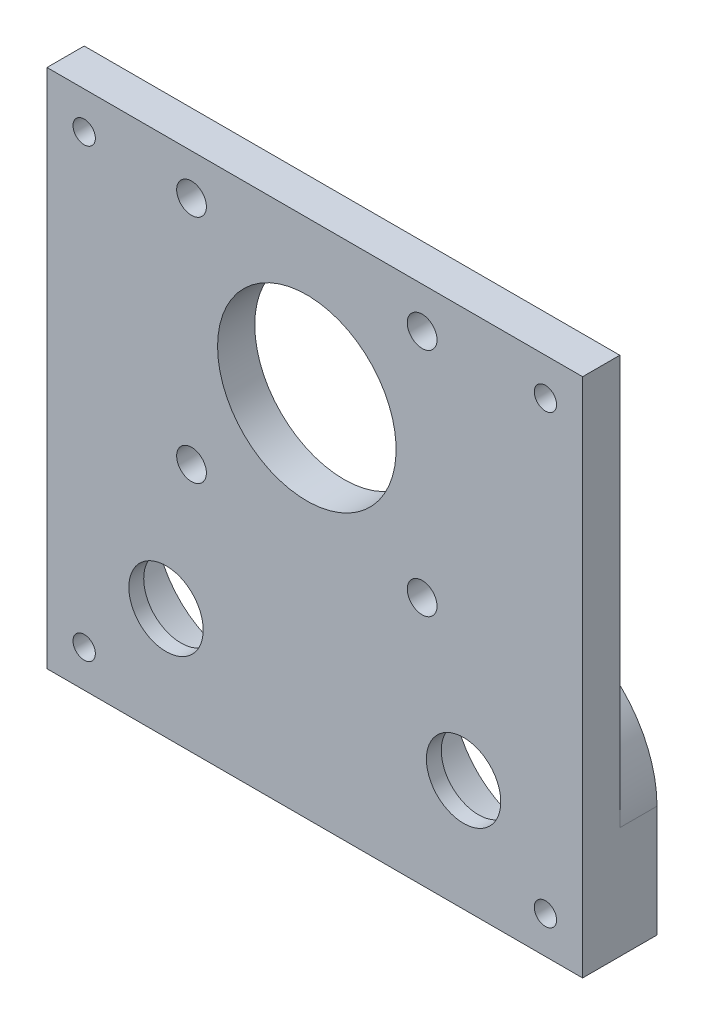
SolidWorks part; units mm, degrees
ref_plane "Front Plane" through (0, 0, 0) normal (0, 0, 1) x (1, 0, 0)
ref_plane "Top Plane" through (0, 0, 0) normal (0, 1, 0) x (1, 0, 0)
ref_plane "Right Plane" through (0, 0, 0) normal (1, 0, 0) x (0, 0, -1)
sketch "Sketch1" plane through (0, 0, 0) normal (0, 0, 1) x (1, 0, 0)
  line L1 (0, 0) -> (70, 0)
  line L2 (0, 0) -> (0, 70)
  line L3 (0, 70) -> (70, 70)
  line L4 (70, 0) -> (70, 70)
  dimension "D1" = 70
  dimension "D2" = 70
extrude "Boss-Extrude1" add sketch "Sketch1" along normal blind 10
sketch "Sketch2" plane through (0, 0, 10) normal (0, 0, 1) x (1, 0, 0)
  line L0 (70, 70) -> (0, 70) construction
  circle A0 centre (35, 49) radius 12
  circle A1 centre (19.5, 65) radius 2
  circle A2 centre (50.5, 65) radius 2
  circle A3 centre (19.5, 34) radius 2
  circle A4 centre (50.5, 34) radius 2
  circle A5 centre (15, 15) radius 11.5
  circle A6 centre (55, 15) radius 11.5
  point P17 (35, 70)
  dimension "D1" = 24
  dimension "D2" = 4
  dimension "D3" = 4
  dimension "D4" = 4
  dimension "D5" = 4
  dimension "D15" = 23
  dimension "D16" = 23
  dimension "D6" = 21
  dimension "D7" = 5
  dimension "D8" = 5
  dimension "D9" = 31
  dimension "D10" = 31
  dimension "D11" = 31
  dimension "D12" = 31
  dimension "D13" = 15.5
  dimension "D14" = 0
  dimension "D17" = 40
  dimension "D18" = 15
  dimension "D19" = 15
  dimension "D20" = 15
extrude "Cut-Extrude1" cut sketch "Sketch2" against normal blind 10
sketch "Sketch3" plane through (0, 0, 0) normal (-1, 0, 0) x (0, 0, 1)
  line L1 (0, 70) -> (10, 70)
  line L2 (0, 70) -> (0, 0)
  line L3 (0, 0) -> (10, 0)
  line L4 (10, 70) -> (10, 0)
extrude "Boss-Extrude2" add sketch "Sketch3" along normal blind 15
sketch "Sketch4" plane through (70, 0, 0) normal (1, 0, 0) x (0, 0, -1)
  line L1 (0, 70) -> (-10, 70)
  line L2 (0, 70) -> (0, 0)
  line L3 (0, 0) -> (-10, 0)
  line L4 (-10, 70) -> (-10, 0)
extrude "Boss-Extrude3" add sketch "Sketch4" along normal blind 15 contours L4 L3 L2 L1
sketch "Sketch5" plane through (0, 0, 10) normal (0, 0, 1) x (1, 0, 0)
  circle A0 centre (15, 15) radius 11.5
  circle A1 centre (55, 15) radius 11.5
  circle A2 centre (15, 15) radius 4
  circle A3 centre (55, 15) radius 4
  dimension "D1" = 8
  dimension "D2" = 8
extrude "Boss-Extrude4" add sketch "Sketch5" against normal blind 2
sketch "Sketch6" plane through (0, 0, 0) normal (0, 0, -1) x (-1, 0, 0)
  line L0 (-85, 70) -> (-85, 0) construction
  line L1 (-85, 70) -> (15, 70) construction
  circle A0 centre (-80, 65) radius 1.5
  circle A1 centre (-80, 5) radius 1.5
  circle A2 centre (10, 65) radius 1.6487
  circle A3 centre (10, 5) radius 1.5
  dimension "D4" = 3
  dimension "D5" = 3
  dimension "D8" = 3
  dimension "D1" = 5
  dimension "D2" = 5
  dimension "D3" = 5
  dimension "D6" = 5
  dimension "D7" = 5
extrude "Cut-Extrude3" cut sketch "Sketch6" against normal blind 10
sketch "Sketch7" plane through (0, 0, 0) normal (0, 0, -1) x (-1, 0, 0)
  circle A0 centre (-35, 49) radius 11.9867
  circle A1 centre (-50.5, 65) radius 2
  circle A2 centre (-19.5, 65) radius 2
  circle A3 centre (-19.5, 34) radius 2
  circle A4 centre (-50.5, 34) radius 2
extrude "Boss-Extrude5" add sketch "Sketch7" against normal blind 10
sketch "Sketch8" plane through (0, 0, 0) normal (0, 0, -1) x (-1, 0, 0)
  line L0 (-85, 70) -> (15, 70) construction
  circle A0 centre (-33.9287, 49) radius 12
  circle A3 centre (-55, 15) radius 4 construction
  dimension "D1" = 24
  dimension "D2" = 21
  dimension "D3" = 40
extrude "Cut-Extrude4" cut sketch "Sketch8" against normal blind 10
sketch "Sketch9" plane through (0, 0, 0) normal (0, 0, -1) x (-1, 0, 0)
  circle A0 centre (-49.4287, 64.5) radius 2
  arc A1 (-34.4643, 37.012) -> (-34.4643, 60.988) centre (-33.9287, 49) ccw construction
  circle A2 centre (-49.4287, 33.5) radius 2
  circle A3 centre (-18.4287, 33.5) radius 2
  circle A4 centre (-18.4287, 64.5) radius 2
  point P5 (-21.9287, 49)
  dimension "D3" = 4
  dimension "D5" = 4
  dimension "D6" = 4
  dimension "D8" = 4
  dimension "D1" = 15.5
  dimension "D2" = 15.5
  dimension "D4" = 31
  dimension "D7" = 31
extrude "Cut-Extrude5" cut sketch "Sketch9" against normal blind 10
sketch "Sketch14" plane through (0, 0, 0) normal (0, 0, -1) x (-1, 0, 0)
  line L0 (-85, 0) -> (-85, 70)
  line L1 (-85, 70) -> (15, 70)
  line L2 (15, 70) -> (15, 0)
  line L3 (15, 70) -> (15, 0) construction
  line L4 (15, 0) -> (-85, 0) construction
  line L5 (-71, 15) -> (-71, 0)
  line L6 (-71, 0) -> (-85, 0)
  line L7 (-39, 15) -> (-39, 0)
  line L8 (-39, 0) -> (-31, 0)
  line L9 (-31, 0) -> (-31, 15)
  line L10 (1, 15) -> (1, 0)
  line L11 (1, 0) -> (15, 0)
  arc A0 (-31, 15) -> (1, 15) centre (-15, 15) cw
  arc A1 (-39, 15) -> (-71, 15) centre (-55, 15) ccw
  dimension "D1" = 16
  dimension "D2" = 16
extrude "Cut-Extrude7" cut sketch "Sketch14" against normal blind 5 contours L2 L11 L10 A0 L9 L8 L7 A1 L5 L6 L0 L1
sketch "Sketch15" plane through (0, 0, 5) normal (0, 0, -1) x (-1, 0, 0)
  line L1 (-71, 0) -> (-85, 0)
  line L2 (-71, 0) -> (-71, 70)
  line L3 (-71, 70) -> (-85, 70)
  line L4 (-85, 0) -> (-85, 70)
  line L5 (1, 0) -> (15, 0)
  line L6 (1, 0) -> (1, 70)
  line L7 (1, 70) -> (15, 70)
  line L8 (15, 0) -> (15, 70)
extrude "Cut-Extrude8" cut sketch "Sketch15" against normal blind 5
sketch "Sketch16" plane through (0, 0, 5) normal (0, 0, -1) x (-1, 0, 0)
  line L0 (-71, 70) -> (1, 70) construction
  line L1 (-71, 15) -> (-71, 70) construction
  line L2 (-39, 0) -> (-71, 0) construction
  line L4 (1, 15) -> (1, 0) construction
  circle A0 centre (-66, 65) radius 1.5
  circle A1 centre (-66, 5) radius 1.5
  circle A2 centre (-4, 5) radius 1.5
  circle A3 centre (-4, 65) radius 1.5
  dimension "D1" = 3
  dimension "D5" = 3
  dimension "D6" = 3
  dimension "D8" = 3
  dimension "D2" = 5
  dimension "D3" = 5
  dimension "D4" = 5
  dimension "D7" = 5
extrude "Cut-Extrude9" cut sketch "Sketch16" along normal blind 19 and the other way blind 48
sketch "Sketch17" plane through (0, 0, 8) normal (0, 0, -1) x (-1, 0, 0)
  circle A0 centre (-15, 15) radius 5
  circle A1 centre (-55, 15) radius 5
  dimension "D1" = 10
  dimension "D2" = 10
extrude "Cut-Extrude10" cut sketch "Sketch17" against normal blind 19
sketch "Sketch18" plane through (0, 0, 5) normal (0, 0, -1) x (-1, 0, 0)
  circle A0 centre (-33.9287, 49) radius 12
  circle A1 centre (-33.9287, 49) radius 16.2892
extrude "Boss-Extrude6" add sketch "Sketch18" against normal blind 5
